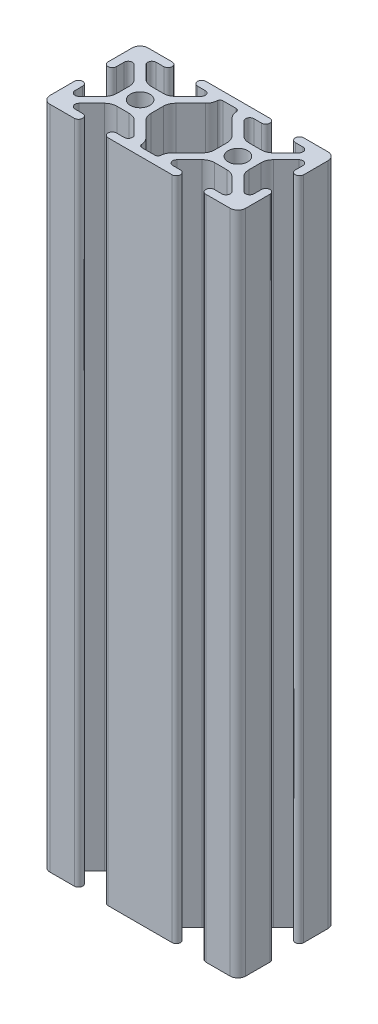
SolidWorks part; units mm, degrees
material "6061-T6 (SS)"
ref_plane "Front Plane" through (0, 0, 0) normal (0, 0, 1) x (1, 0, 0)
ref_plane "Top Plane" through (0, 0, 0) normal (0, 1, 0) x (1, 0, 0)
ref_plane "Right Plane" through (0, 0, 0) normal (1, 0, 0) x (0, 0, -1)
sketch "Sketch1" plane through (0, 0, 0) normal (0, 0, 1) x (1, 0, 0)
  line L0 (0, 0) -> (0, 170)
  dimension "D1" = 170
other "25 series extrusions 25-2550(1)"
ref_plane "Plane1" through (0, 0, 0) normal (0, 1, 0) x (-1, 0, 0)
sketch "Sketch11" plane through (0, 0, 0) normal (0, 1, 0) x (-1, 0, 0)
  line L0 (-1.6788, 10.37) -> (1.6788, 10.37)
  line L1 (3.3613, 7.6351) -> (7.1912, 3.8052)
  line L2 (8.1211, 1.5602) -> (8.1211, -1.5602)
  line L3 (7.1912, -3.8052) -> (3.3613, -7.6351)
  line L4 (1.6788, -10.37) -> (-1.6788, -10.37)
  line L5 (-3.3613, -7.6351) -> (-7.1912, -3.8052)
  line L6 (-8.1211, -1.5602) -> (-8.1211, 1.5602)
  line L7 (-7.1912, 3.8052) -> (-3.3613, 7.6351)
  line L8 (8.185, 12.5) -> (-8.185, 12.5)
  line L9 (-8.185, 10.37) -> (-6.2272, 10.37)
  line L10 (-5.469, 8.5396) -> (-8.6976, 5.311)
  line L11 (-10.9427, 4.3811) -> (-14.0573, 4.3811)
  line L12 (-16.3024, 5.311) -> (-19.531, 8.5396)
  line L13 (-18.7728, 10.37) -> (-16.815, 10.37)
  line L14 (-16.815, 12.5) -> (-23, 12.5)
  line L15 (-25, 10.5) -> (-25, 4.315)
  line L16 (-22.87, 4.315) -> (-22.87, 6.2728)
  line L17 (-21.0396, 7.031) -> (-17.811, 3.8024)
  line L18 (-16.8811, 1.5573) -> (-16.8811, -1.5573)
  line L19 (-17.811, -3.8024) -> (-21.0396, -7.031)
  line L20 (-22.87, -6.2728) -> (-22.87, -4.315)
  line L21 (-25, -4.315) -> (-25, -10.5)
  line L22 (-23, -12.5) -> (-16.815, -12.5)
  line L23 (-16.815, -10.37) -> (-18.7728, -10.37)
  line L24 (-19.531, -8.5396) -> (-16.3024, -5.311)
  line L25 (-14.0573, -4.3811) -> (-10.9427, -4.3811)
  line L26 (-8.6976, -5.311) -> (-5.469, -8.5396)
  line L27 (-6.2272, -10.37) -> (-8.185, -10.37)
  line L28 (-8.185, -12.5) -> (8.185, -12.5)
  line L29 (8.185, -10.37) -> (6.2272, -10.37)
  line L30 (5.469, -8.5396) -> (8.6976, -5.311)
  line L31 (10.9427, -4.3811) -> (14.0573, -4.3811)
  line L32 (16.3024, -5.311) -> (19.531, -8.5396)
  line L33 (18.7728, -10.37) -> (16.815, -10.37)
  line L34 (16.815, -12.5) -> (23, -12.5)
  line L35 (25, -10.5) -> (25, -4.315)
  line L36 (22.87, -4.315) -> (22.87, -6.2728)
  line L37 (21.0396, -7.031) -> (17.811, -3.8024)
  line L38 (16.8811, -1.5573) -> (16.8811, 1.5573)
  line L39 (17.811, 3.8024) -> (21.0396, 7.031)
  line L40 (22.87, 6.2728) -> (22.87, 4.315)
  line L41 (25, 4.315) -> (25, 10.5)
  line L42 (23, 12.5) -> (16.815, 12.5)
  line L43 (16.815, 10.37) -> (18.7728, 10.37)
  line L44 (19.531, 8.5396) -> (16.3024, 5.311)
  line L45 (14.0573, 4.3811) -> (10.9427, 4.3811)
  line L46 (8.6976, 5.311) -> (5.469, 8.5396)
  line L47 (6.2272, 10.37) -> (8.185, 10.37)
  circle A0 centre (-12.5, 0) radius 2.5
  circle A1 centre (12.5, 0) radius 2.5
  arc A2 (-1.6788, 10.37) -> (-2.439, 9.6607) centre (-1.6788, 9.608) ccw
  arc A3 (2.439, 9.6607) -> (1.6788, 10.37) centre (1.6788, 9.608) ccw
  arc A4 (2.439, 9.6607) -> (3.3613, 7.6351) centre (5.6064, 9.8802) ccw
  arc A5 (8.1211, 1.5602) -> (7.1912, 3.8052) centre (4.9461, 1.5602) ccw
  arc A6 (7.1912, -3.8052) -> (8.1211, -1.5602) centre (4.9461, -1.5602) ccw
  arc A7 (3.3613, -7.6351) -> (2.439, -9.6607) centre (5.6064, -9.8802) ccw
  arc A8 (1.6788, -10.37) -> (2.439, -9.6607) centre (1.6788, -9.608) ccw
  arc A9 (-2.439, -9.6607) -> (-1.6788, -10.37) centre (-1.6788, -9.608) ccw
  arc A10 (-2.439, -9.6607) -> (-3.3613, -7.6351) centre (-5.6064, -9.8802) ccw
  arc A11 (-8.1211, -1.5602) -> (-7.1912, -3.8052) centre (-4.9461, -1.5602) ccw
  arc A12 (-7.1912, 3.8052) -> (-8.1211, 1.5602) centre (-4.9461, 1.5602) ccw
  arc A13 (-3.3613, 7.6351) -> (-2.439, 9.6607) centre (-5.6064, 9.8802) ccw
  arc A14 (-8.185, 12.5) -> (-8.185, 10.37) centre (-8.185, 11.435) ccw
  arc A15 (-5.469, 8.5396) -> (-6.2272, 10.37) centre (-6.2272, 9.2978) ccw
  arc A16 (-10.9427, 4.3811) -> (-8.6976, 5.311) centre (-10.9427, 7.5561) ccw
  arc A17 (-16.3024, 5.311) -> (-14.0573, 4.3811) centre (-14.0573, 7.5561) ccw
  arc A18 (-18.7728, 10.37) -> (-19.531, 8.5396) centre (-18.7728, 9.2978) ccw
  arc A19 (-16.815, 10.37) -> (-16.815, 12.5) centre (-16.815, 11.435) ccw
  arc A20 (-23, 12.5) -> (-25, 10.5) centre (-23, 10.5) ccw
  arc A21 (-25, 4.315) -> (-22.87, 4.315) centre (-23.935, 4.315) ccw
  arc A22 (-21.0396, 7.031) -> (-22.87, 6.2728) centre (-21.7978, 6.2728) ccw
  arc A23 (-16.8811, 1.5573) -> (-17.811, 3.8024) centre (-20.0561, 1.5573) ccw
  arc A24 (-17.811, -3.8024) -> (-16.8811, -1.5573) centre (-20.0561, -1.5573) ccw
  arc A25 (-22.87, -6.2728) -> (-21.0396, -7.031) centre (-21.7978, -6.2728) ccw
  arc A26 (-22.87, -4.315) -> (-25, -4.315) centre (-23.935, -4.315) ccw
  arc A27 (-25, -10.5) -> (-23, -12.5) centre (-23, -10.5) ccw
  arc A28 (-16.815, -12.5) -> (-16.815, -10.37) centre (-16.815, -11.435) ccw
  arc A29 (-19.531, -8.5396) -> (-18.7728, -10.37) centre (-18.7728, -9.2978) ccw
  arc A30 (-14.0573, -4.3811) -> (-16.3024, -5.311) centre (-14.0573, -7.5561) ccw
  arc A31 (-8.6976, -5.311) -> (-10.9427, -4.3811) centre (-10.9427, -7.5561) ccw
  arc A32 (-6.2272, -10.37) -> (-5.469, -8.5396) centre (-6.2272, -9.2978) ccw
  arc A33 (-8.185, -10.37) -> (-8.185, -12.5) centre (-8.185, -11.435) ccw
  arc A34 (8.185, -12.5) -> (8.185, -10.37) centre (8.185, -11.435) ccw
  arc A35 (5.469, -8.5396) -> (6.2272, -10.37) centre (6.2272, -9.2978) ccw
  arc A36 (10.9427, -4.3811) -> (8.6976, -5.311) centre (10.9427, -7.5561) ccw
  arc A37 (16.3024, -5.311) -> (14.0573, -4.3811) centre (14.0573, -7.5561) ccw
  arc A38 (18.7728, -10.37) -> (19.531, -8.5396) centre (18.7728, -9.2978) ccw
  arc A39 (16.815, -10.37) -> (16.815, -12.5) centre (16.815, -11.435) ccw
  arc A40 (23, -12.5) -> (25, -10.5) centre (23, -10.5) ccw
  arc A41 (25, -4.315) -> (22.87, -4.315) centre (23.935, -4.315) ccw
  arc A42 (21.0396, -7.031) -> (22.87, -6.2728) centre (21.7978, -6.2728) ccw
  arc A43 (16.8811, -1.5573) -> (17.811, -3.8024) centre (20.0561, -1.5573) ccw
  arc A44 (17.811, 3.8024) -> (16.8811, 1.5573) centre (20.0561, 1.5573) ccw
  arc A45 (22.87, 6.2728) -> (21.0396, 7.031) centre (21.7978, 6.2728) ccw
  arc A46 (22.87, 4.315) -> (25, 4.315) centre (23.935, 4.315) ccw
  arc A47 (25, 10.5) -> (23, 12.5) centre (23, 10.5) ccw
  arc A48 (16.815, 12.5) -> (16.815, 10.37) centre (16.815, 11.435) ccw
  arc A49 (19.531, 8.5396) -> (18.7728, 10.37) centre (18.7728, 9.2978) ccw
  arc A50 (14.0573, 4.3811) -> (16.3024, 5.311) centre (14.0573, 7.5561) ccw
  arc A51 (8.6976, 5.311) -> (10.9427, 4.3811) centre (10.9427, 7.5561) ccw
  arc A52 (6.2272, 10.37) -> (5.469, 8.5396) centre (6.2272, 9.2978) ccw
  arc A53 (8.185, 10.37) -> (8.185, 12.5) centre (8.185, 11.435) ccw
  point P0 (0, 0)
